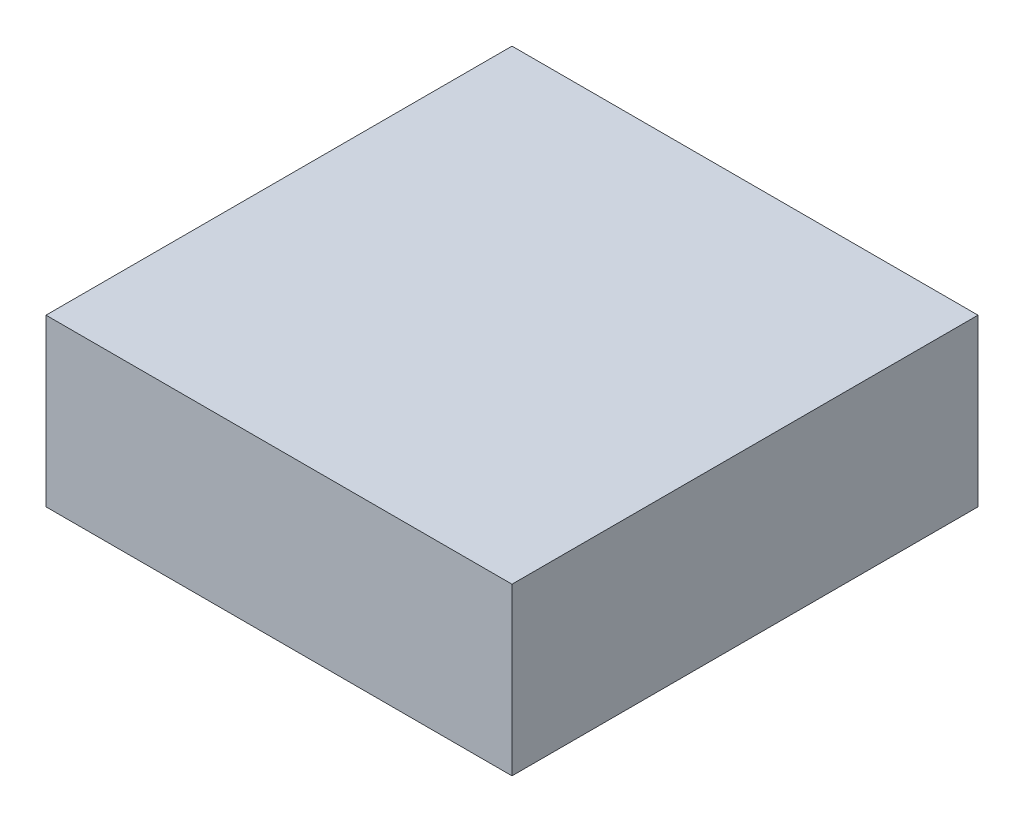
SolidWorks part; units mm, degrees
ref_plane "Front Plane" through (0, 0, 0) normal (0, 0, 1) x (1, 0, 0)
ref_plane "Top Plane" through (0, 0, 0) normal (0, 1, 0) x (1, 0, 0)
ref_plane "Right Plane" through (0, 0, 0) normal (1, 0, 0) x (0, 0, -1)
sketch "Sketch1" plane through (0, 0, 0) normal (0, 1, 0) x (1, 0, 0)
  line L1 (-49.2103, 220.63) -> (204.7897, 220.63)
  line L2 (-49.2103, 220.63) -> (-49.2103, -33.37)
  line L3 (-49.2103, -33.37) -> (204.7897, -33.37)
  line L4 (204.7897, 220.63) -> (204.7897, -33.37)
extrude "Boss-Extrude1" add sketch "Sketch1" along normal blind 90.4875
